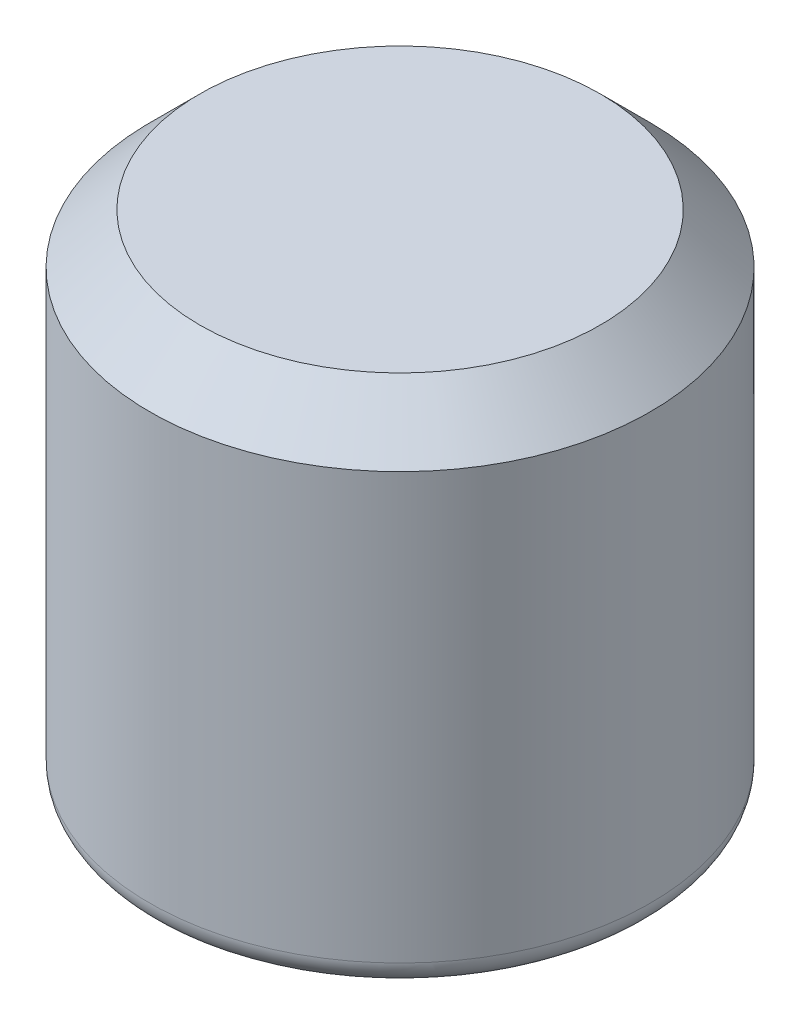
SolidWorks part; units mm, degrees
ref_plane "Front Plane" through (0, 0, 0) normal (0, 0, 1) x (1, 0, 0)
ref_plane "Top Plane" through (0, 0, 0) normal (0, 1, 0) x (1, 0, 0)
ref_plane "Right Plane" through (0, 0, 0) normal (1, 0, 0) x (0, 0, -1)
ref_plane "plane:xy" through (0, 0, 0) normal (0, 0, 1) x (1, 0, 0)
sketch "sketch:profile" plane through (0, 0, 0) normal (0, 0, 1) x (1, 0, 0)
  line L0 (0, 0) -> (10, 0)
  line L1 (10, 0) -> (10, 18)
  line L2 (10, 18) -> (8, 20)
  line L3 (8, 20) -> (0, 20)
  line L4 (0, 20) -> (0, 0)
  line L5 (0, -10) -> (0, 30) construction
revolve "feature:turned" add sketch "sketch:profile" angle 360 about L5
fillet "feature:round" radius 1 1 edges at (0, 0, -10)
sketch "sketch:helper-0" plane through (0, 0, 0) normal (0, 0, 1) x (1, 0, 0)
  line L0 (30, 0) -> (40, 0)
sketch "sketch:helper-1" plane through (0, 0, 0) normal (0, 0, 1) x (1, 0, 0)
  line L0 (30, 5) -> (40, 5)
